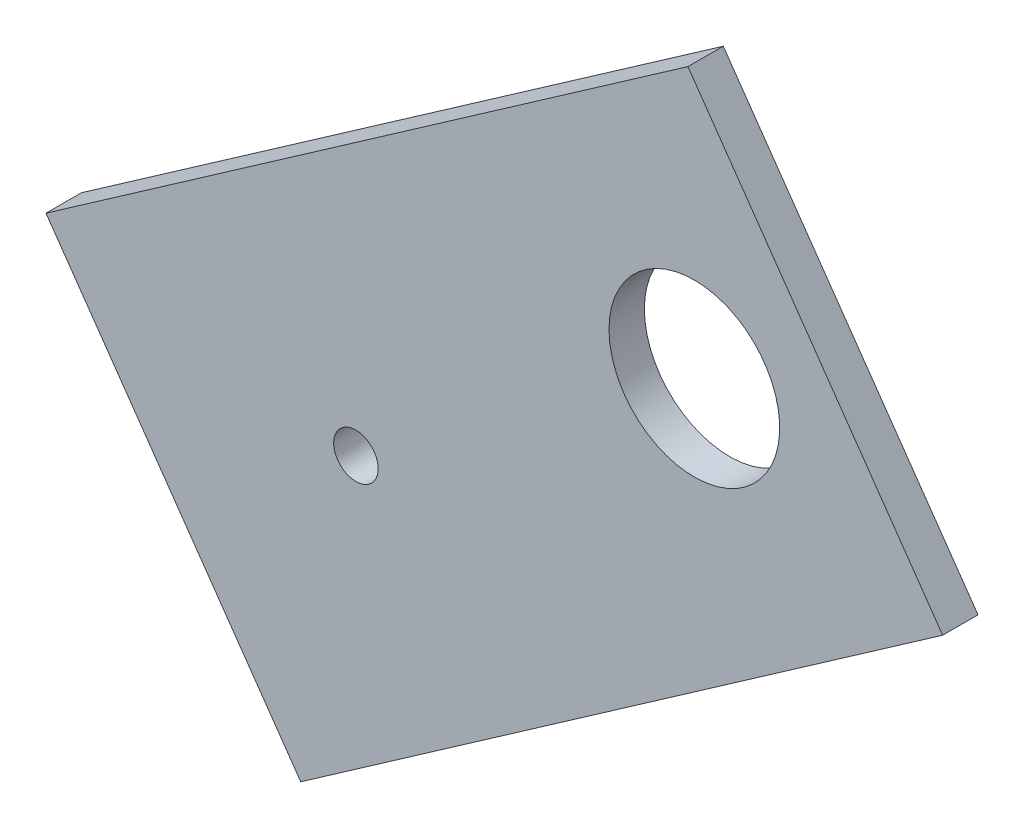
SolidWorks part; units mm, degrees
ref_plane "Front Plane" through (0, 0, 0) normal (0, 0, 1) x (1, 0, 0)
ref_plane "Top Plane" through (0, 0, 0) normal (0, 1, 0) x (1, 0, 0)
ref_plane "Right Plane" through (0, 0, 0) normal (1, 0, 0) x (0, 0, -1)
sketch "Sketch1" plane through (0, 0, 0) normal (0, 0, 1) x (1, 0, 0)
  line L0 (13.0096, -14.2343) -> (-21.3223, 34.9727) construction
  line L1 (21.9366, 65.1546) -> (-64.5812, 4.7907)
  line L2 (21.9366, 65.1546) -> (56.2685, 15.9477)
  line L3 (56.2685, 15.9477) -> (-30.2493, -44.4162)
  line L4 (-64.5812, 4.7907) -> (-30.2493, -44.4162)
  line L5 (22.8, 29.1768) -> (-22.8118, -2.6468) construction
  circle A0 centre (-22.8118, -2.6468) radius 3
  circle A1 centre (22.8, 29.1768) radius 11.5
  circle A2 centre (22.8, 29.1768) radius 11.5 construction
  circle A5 centre (-22.8118, -2.6468) radius 3 construction
  dimension "D1" = 60
  dimension "D2" = 30
extrude "Boss-Extrude1" add sketch "Sketch1" along normal blind 4.7625
